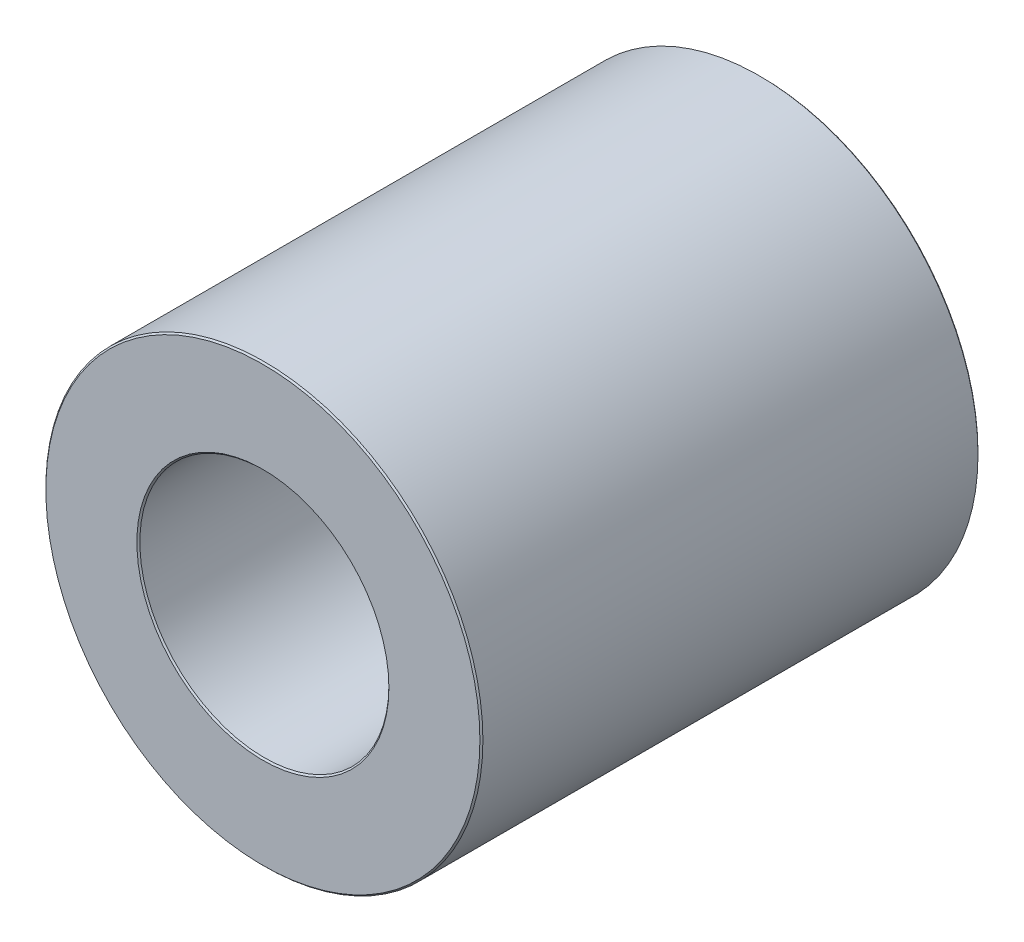
SolidWorks part; units mm, degrees
ref_plane "Front Plane" through (0, 0, 0) normal (0, 0, 1) x (1, 0, 0)
ref_plane "Top Plane" through (0, 0, 0) normal (0, 1, 0) x (1, 0, 0)
ref_plane "Right Plane" through (0, 0, 0) normal (1, 0, 0) x (0, 0, -1)
sketch "Sketch1" plane through (0, 0, 0) normal (0, 0, 1) x (1, 0, 0)
  circle A0 centre (0, 0) radius 3.51
  circle A1 centre (0, 0) radius 2
  point P8 (0, -3.51)
  point P9 (0, 3.51)
  dimension "ID" = 4
  dimension "OD" = 7.02
sketch "Sketch2" plane through (0, 0, 0) normal (1, 0, 0) x (0, 0, -1)
  line L0 (4, 0) -> (-4, 0) construction
  line L1 (4, 3.51) -> (-4, 3.51) construction
  point P4 (0, 0)
  point P8 (0, 3.51)
  point P9 (0, 3.51)
  dimension "Length" = 8
sketch "Sketch5" plane through (0, 0, 0) normal (0, 0, 1) x (1, 0, 0)
  circle A0 centre (0, 0) radius 2 construction
  circle A1 centre (0, 0) radius 3.51 construction
  circle A2 centre (0, 0) radius 2
  circle A3 centre (0, 0) radius 3.51
extrude "Boss-Extrude1" add sketch "Sketch5" along normal up to vertex (4 mm away) and the other way up to vertex (4 mm away) up to point (0, 0, 4) other way up to point (0, 0, -4)
chamfer "Chamfer1" distance 0.024 angle 45 4 edges at (3.51, 0, -4) (2, 0, -4) (2, 0, 4) (3.51, 0, 4)
equation "\"D1@Chamfer1\"=\"ID@Sketch1\"*.006"
